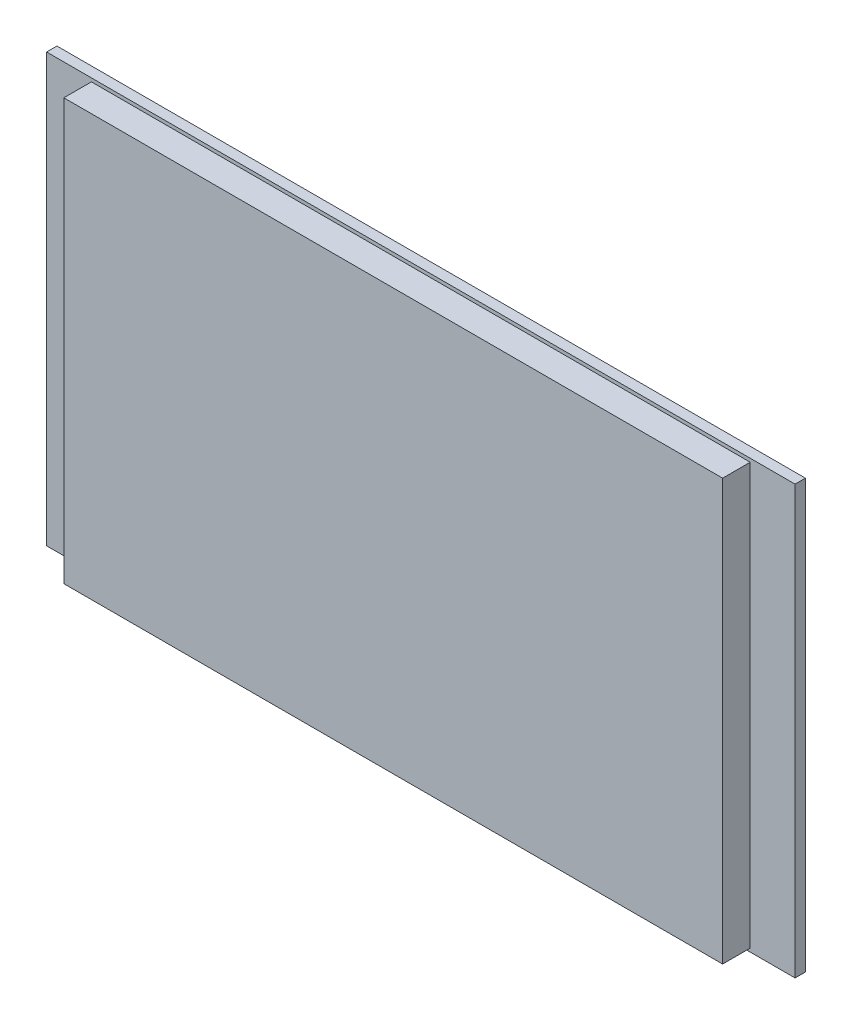
SolidWorks part; units mm, degrees
ref_plane "Plan de face" through (0, 0, 0) normal (0, 0, 1) x (1, 0, 0)
ref_plane "Plan de dessus" through (0, 0, 0) normal (0, 1, 0) x (1, 0, 0)
ref_plane "Plan de droite" through (0, 0, 0) normal (1, 0, 0) x (0, 0, -1)
sketch "Esquisse1" plane through (0, 0, 0) normal (0, 0, 1) x (1, 0, 0)
  line L0 (-47.75, 0) -> (0, 0) construction
  line L1 (-47.75, 30.5) -> (47.75, 30.5)
  line L2 (-47.75, 30.5) -> (-47.75, -30.5)
  line L3 (-47.75, -30.5) -> (47.75, -30.5)
  line L4 (47.75, 30.5) -> (47.75, -30.5)
  line L5 (0, 0) -> (47.75, 0) construction
  line L6 (0, 0) -> (0, 30.5) construction
  line L7 (0, 0) -> (0, -30.5) construction
  dimension "D1" = 95.5
  dimension "D2" = 61
extrude "Boss.-Extru.1" add sketch "Esquisse1" along normal blind 4
sketch "Esquisse2" plane through (0, 0, 0) normal (0, 0, -1) x (-1, 0, 0)
  line L0 (0, 31) -> (0, 0) construction
  line L1 (-54.25, 31) -> (54.25, 31)
  line L2 (-54.25, 31) -> (-54.25, -31)
  line L3 (-54.25, -31) -> (54.25, -31)
  line L12 (54.25, 31) -> (54.25, -31)
  line L13 (0, 0) -> (0, -31) construction
  line L15 (0, 0) -> (-54.25, 0) construction
  line L17 (0, 0) -> (54.25, 0) construction
  dimension "D2" = 62
  dimension "D1" = 108.5
extrude "Boss.-Extru.2" add sketch "Esquisse2" along normal blind 1.5
sketch "Esquisse3" plane through (0, 0, -1.5) normal (0, 0, -1) x (-1, 0, 0)
  line L2 (53.75, 17.75) -> (53.75, -17.75)
  line L3 (53.75, -17.75) -> (51.25, -17.75)
  line L4 (51.25, 17.75) -> (51.25, -17.75)
  line L5 (52.5, 17.75) -> (52.5, 31)
  line L6 (54.25, 31) -> (-54.25, 31) construction
  line L7 (52.5, -17.75) -> (52.5, -31)
  line L8 (-54.25, -31) -> (54.25, -31) construction
  line L9 (54.25, -31) -> (54.25, 31) construction
  line L10 (53.75, 17.75) -> (51.25, 17.75)
  dimension "D1" = 35.5
  dimension "D2" = 0.5
  dimension "D3" = 2.5
extrude "Boss.-Extru.3" add sketch "Esquisse3" along normal blind 3 contours L10 L4 L3 L2
sketch "Esquisse4" plane through (0, 0, -4.5) normal (0, 0, -1) x (-1, 0, 0)
  line L0 (53.75, 17.75) -> (51.25, 17.75) construction
  line L1 (52.175, 16.45) -> (52.825, 16.45)
  line L2 (52.175, 16.45) -> (52.175, 17.1)
  line L3 (52.175, 17.1) -> (52.825, 17.1)
  line L4 (52.825, 16.45) -> (52.825, 17.1)
  line L5 (52.175, 13.95) -> (52.175, 14.6)
  line L6 (52.175, 13.95) -> (52.825, 13.95)
  line L7 (52.175, 16.775) -> (51.25, 16.775) construction
  line L8 (51.25, 17.75) -> (51.25, -17.75) construction
  line L9 (52.825, 16.775) -> (53.75, 16.775) construction
  line L10 (53.75, 17.75) -> (53.75, -17.75) construction
  line L11 (52.825, 13.95) -> (52.825, 14.6)
  line L12 (52.175, 14.6) -> (52.825, 14.6)
  line L13 (52.175, 11.45) -> (52.175, 12.1)
  line L14 (52.175, 11.45) -> (52.825, 11.45)
  line L15 (52.825, 11.45) -> (52.825, 12.1)
  line L16 (52.175, 12.1) -> (52.825, 12.1)
  line L17 (52.175, 8.95) -> (52.175, 9.6)
  line L18 (52.175, 8.95) -> (52.825, 8.95)
  line L19 (52.825, 8.95) -> (52.825, 9.6)
  line L20 (52.175, 9.6) -> (52.825, 9.6)
  line L21 (52.175, 6.45) -> (52.175, 7.1)
  line L22 (52.175, 6.45) -> (52.825, 6.45)
  line L23 (52.825, 6.45) -> (52.825, 7.1)
  line L24 (52.175, 7.1) -> (52.825, 7.1)
  line L25 (52.175, 3.95) -> (52.175, 4.6)
  line L26 (52.175, 3.95) -> (52.825, 3.95)
  line L27 (52.825, 3.95) -> (52.825, 4.6)
  line L28 (52.175, 4.6) -> (52.825, 4.6)
  line L29 (52.175, 1.45) -> (52.175, 2.1)
  line L30 (52.175, 1.45) -> (52.825, 1.45)
  line L31 (52.825, 1.45) -> (52.825, 2.1)
  line L32 (52.175, 2.1) -> (52.825, 2.1)
  line L33 (52.175, -1.05) -> (52.175, -0.4)
  line L34 (52.175, -1.05) -> (52.825, -1.05)
  line L35 (52.825, -1.05) -> (52.825, -0.4)
  line L36 (52.175, -0.4) -> (52.825, -0.4)
  line L37 (52.175, -3.55) -> (52.175, -2.9)
  line L38 (52.175, -3.55) -> (52.825, -3.55)
  line L39 (52.825, -3.55) -> (52.825, -2.9)
  line L40 (52.175, -2.9) -> (52.825, -2.9)
  line L41 (52.175, -6.05) -> (52.175, -5.4)
  line L42 (52.175, -6.05) -> (52.825, -6.05)
  line L43 (52.825, -6.05) -> (52.825, -5.4)
  line L44 (52.175, -5.4) -> (52.825, -5.4)
  line L45 (52.175, -8.55) -> (52.175, -7.9)
  line L46 (52.175, -8.55) -> (52.825, -8.55)
  line L47 (52.825, -8.55) -> (52.825, -7.9)
  line L48 (52.175, -7.9) -> (52.825, -7.9)
  line L49 (52.175, -11.05) -> (52.175, -10.4)
  line L50 (52.175, -11.05) -> (52.825, -11.05)
  line L51 (52.825, -11.05) -> (52.825, -10.4)
  line L52 (52.175, -10.4) -> (52.825, -10.4)
  line L53 (52.175, -13.55) -> (52.175, -12.9)
  line L54 (52.175, -13.55) -> (52.825, -13.55)
  line L55 (52.825, -13.55) -> (52.825, -12.9)
  line L56 (52.175, -12.9) -> (52.825, -12.9)
  line L57 (52.175, -16.05) -> (52.175, -15.4)
  line L58 (52.175, -16.05) -> (52.825, -16.05)
  line L59 (52.825, -16.05) -> (52.825, -15.4)
  line L60 (52.175, -15.4) -> (52.825, -15.4)
  dimension "D1" = 0.65
  dimension "D2" = 0.65
  dimension "D3" = 0.65
  dimension "D4" = 14
extrude "Boss.-Extru.4" add sketch "Esquisse4" along normal blind 5.5
